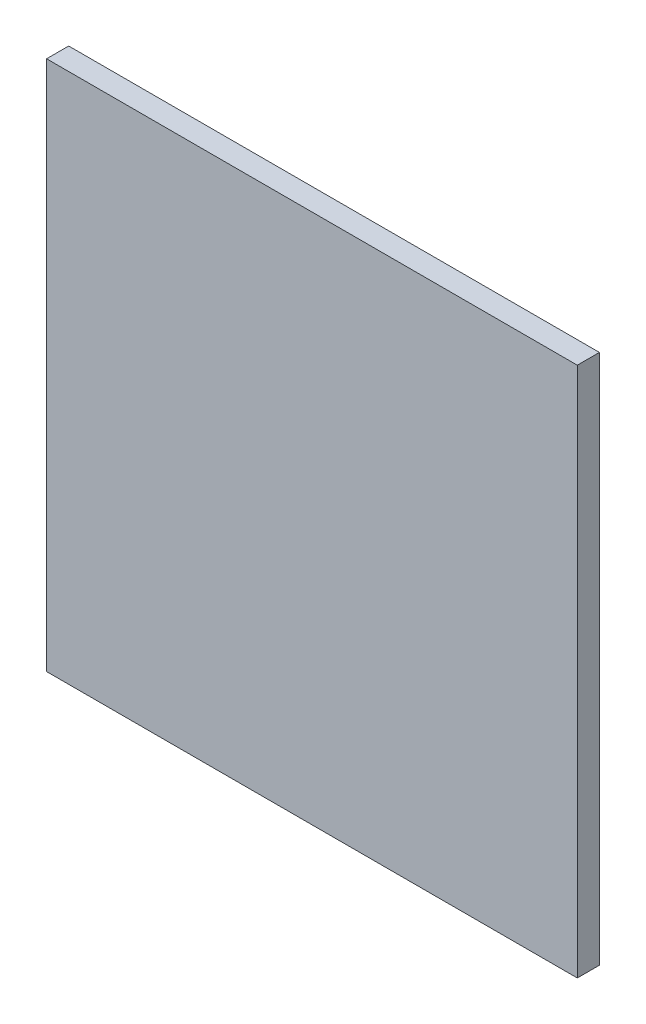
SolidWorks part; units mm, degrees
ref_plane "Front Plane" through (0, 0, 0) normal (0, 0, 1) x (1, 0, 0)
ref_plane "Top Plane" through (0, 0, 0) normal (0, 1, 0) x (1, 0, 0)
ref_plane "Right Plane" through (0, 0, 0) normal (1, 0, 0) x (0, 0, -1)
sketch "Sketch1" plane through (0, 0, 0) normal (0, 0, 1) x (1, 0, 0)
  line L0 (55, 0) -> (-55, 0) construction
  line L1 (-1524, -1524) -> (1524, -1524)
  line L2 (-1524, -1524) -> (-1524, 1524)
  line L3 (-1524, 1524) -> (1524, 1524)
  line L4 (1524, -1524) -> (1524, 1524)
  dimension "D1" = 3048
  dimension "D2" = 1524
  dimension "D3" = 3048
  dimension "D4" = 1524
extrude "Boss-Extrude1" add sketch "Sketch1" along normal blind 127
